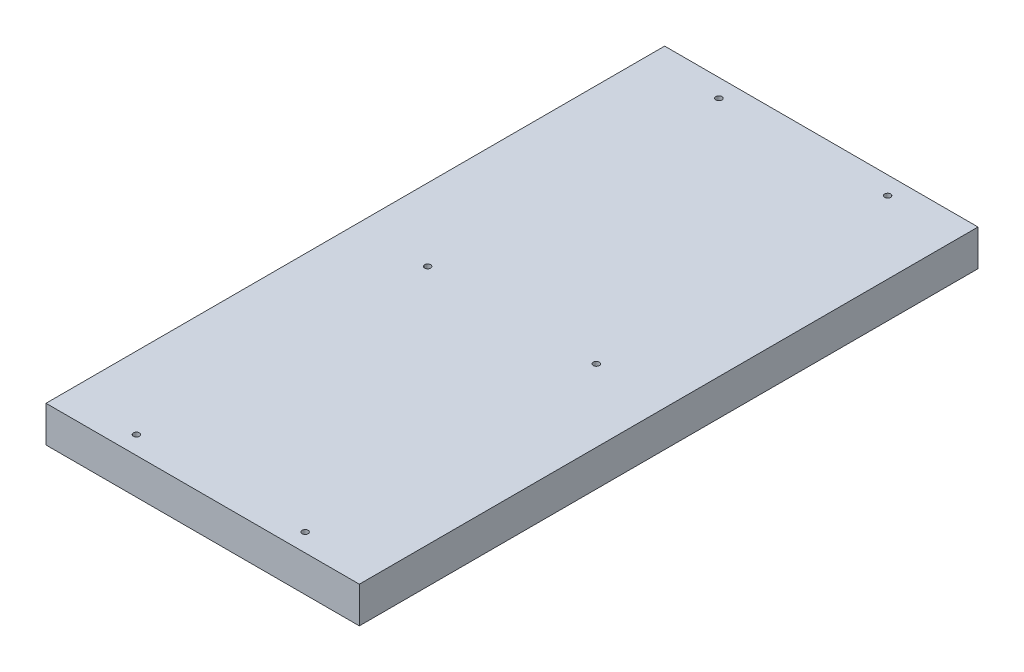
SolidWorks part; units mm, degrees
material "Pin"
ref_plane "Plan de face" through (0, 0, 0) normal (0, 0, 1) x (1, 0, 0)
ref_plane "Plan de dessus" through (0, 0, 0) normal (0, 1, 0) x (1, 0, 0)
ref_plane "Plan de droite" through (0, 0, 0) normal (1, 0, 0) x (0, 0, -1)
sketch "Esquisse1" plane through (0, 0, 0) normal (0, 0, 1) x (1, 0, 0)
  line L1 (-195, -22.5) -> (195, -22.5)
  line L2 (-195, -22.5) -> (-195, 22.5)
  line L3 (-195, 22.5) -> (195, 22.5)
  line L4 (195, -22.5) -> (195, 22.5)
  line L5 (-195, -22.5) -> (195, 22.5) construction
  line L6 (-195, 22.5) -> (195, -22.5) construction
  point P0 (0, 0)
  dimension "D1" = 45
  dimension "D2" = 390
extrude "Boss.-Extru.1" add sketch "Esquisse1" along normal blind 770
sketch "Esquisse2" plane through (0, 22.5, 0) normal (0, 1, 0) x (1, 0, 0)
  line L0 (-195, 0) -> (-195, -22.5) construction
  line L1 (-195, -770) -> (-195, 0) construction
  line L2 (-195, -22.5) -> (-105, -22.5) construction
  line L3 (0, 0) -> (0, -770) construction
  line L4 (195, -770) -> (-195, -770) construction
  line L5 (-195, -385) -> (195, -385) construction
  line L6 (195, -770) -> (195, 0) construction
  line L7 (195, 0) -> (195, -22.5) construction
  line L8 (195, -22.5) -> (105, -22.5) construction
  line L9 (195, -770) -> (195, -747.5) construction
  line L10 (195, -747.5) -> (105, -747.5) construction
  line L11 (-195, -770) -> (-195, -747.5) construction
  line L12 (-195, -747.5) -> (-105, -747.5) construction
  circle A0 centre (-105, -22.5) radius 3.75
  circle A1 centre (105, -22.5) radius 3.75
  circle A2 centre (105, -747.5) radius 3.75
  circle A3 centre (-105, -747.5) radius 3.75
  circle A4 centre (-105, -385) radius 3.75
  circle A5 centre (105, -385) radius 3.75
  dimension "D2" = 7.5
  dimension "D5" = 7.5
  dimension "D6" = 7.5
  dimension "D1" = 90
  dimension "D3" = 22.5
  dimension "D4" = 90
  dimension "D7" = 90
extrude "Enlèv. mat.-Extru.1" cut sketch "Esquisse2" against normal blind 20
sketch "Esquisse3" plane through (0, 22.5, 0) normal (0, 1, 0) x (1, 0, 0)
  circle A0 centre (-105, -385) radius 3.75
  circle A1 centre (105, -385) radius 3.75
extrude "Enlèv. mat.-Extru.2" cut sketch "Esquisse3" against normal blind 30
